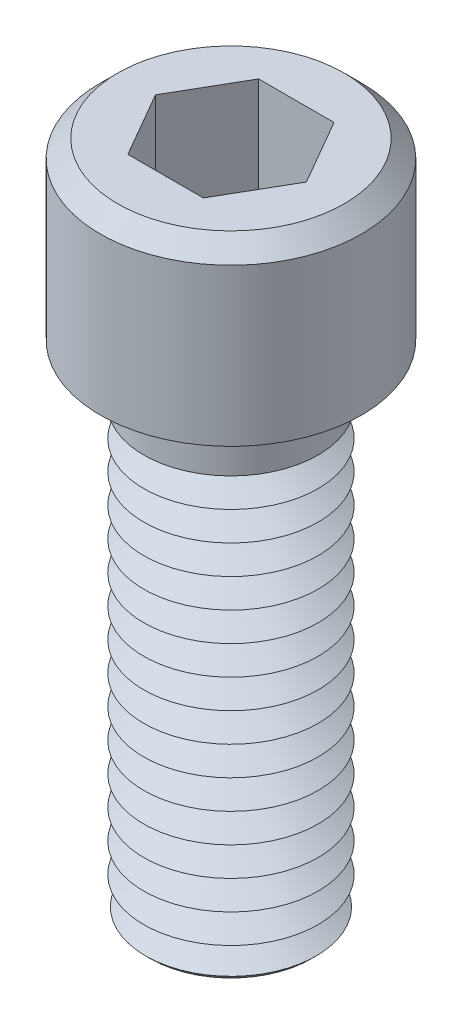
SolidWorks part; units mm, degrees
ref_plane "Front" through (0, 0, 0) normal (0, 0, 1) x (1, 0, 0)
ref_plane "Top" through (0, 0, 0) normal (0, 1, 0) x (1, 0, 0)
ref_plane "Right" through (0, 0, 0) normal (1, 0, 0) x (0, 0, -1)
ref_axis "Axis1" through (0, -50, 0) along (0, 1, 0)
sketch "Sketch ( driver )" plane through (0, 0, 0) normal (0, 0, 1) x (1, 0, 0)
  line L0 (0, 2.1844) -> (1.4199, 2.1844)
  line L1 (1.6383, 1.966) -> (1.4199, 2.1844)
  line L2 (1.6383, 1.966) -> (1.6383, 0)
  line L3 (1.6383, 0) -> (1.0922, 0)
  line L4 (1.0922, 0) -> (1.0922, -6.1316)
  line L5 (1.0922, -6.1316) -> (0.8738, -6.35)
  line L6 (0.8738, -6.35) -> (0, -6.35)
  line L7 (0, -6.35) -> (0, 2.1844)
  line L8 (0, 4.3688) -> (0, 2.1844) construction
  line L9 (1.0922, -0.707) -> (1.0922, -1.071) construction
  line L10 (1.0922, -1.071) -> (0.7769, -0.889) construction
  line L11 (0.7769, -0.889) -> (1.0922, -0.707) construction
  circle A0 centre (0, 2.1844) radius 0.8192 construction
  point P2 (0, 0.6553)
  point P12 (0.8192, 2.1844)
  dimension "D4" = 1.5291
  dimension "D5" = 1.6383
  dimension "D1" = 0.2184
  dimension "Pitch" = 0.3641
  dimension "D2" = 45
  dimension "D3" = 45
  dimension "Diam" = 2.1844
  dimension "Head Dia" = 3.2766
  dimension "Thick" = 2.1844
  dimension "Length" = 6.35
  dimension "End Chamfer" = 0.2184
  dimension "Threaded" = 5.461
sketch "Sketch3" plane through (0, 0, 0) normal (0, 0, 1) x (1, 0, 0)
  line L8 (0, 0.6553) -> (0, -6.35)
  line L9 (0, -6.35) -> (0.8738, -6.35)
  line L10 (0.8738, -6.35) -> (1.0922, -6.1316)
  line L11 (1.0922, -6.1316) -> (1.0922, 0.6553)
  line L12 (1.0922, 0.6553) -> (0, 0.6553)
revolve "Shank Revolve ( driven )" add sketch "Sketch3" angle 360 about axis through (0, -50, 0) along (0, 1, 0)
sketch "Sketch4" plane through (0, 0, 0) normal (0, 0, 1) x (1, 0, 0)
  line L0 (0.7769, -0.889) -> (1.0922, -0.707)
  line L1 (1.0922, -0.707) -> (1.6337, -0.707)
  line L2 (1.6337, -0.707) -> (1.6337, -7.2602)
  line L3 (0.7769, -0.889) -> (1.0922, -1.071)
  line L4 (1.0922, -1.071) -> (0.7769, -1.2531)
  line L5 (0.7769, -1.2531) -> (1.0922, -1.4351)
  line L6 (1.0922, 0) -> (1.0922, -6.1316) construction
  line L7 (1.0922, -1.4351) -> (0.7769, -1.6171)
  line L8 (0.7769, -1.6171) -> (1.0922, -1.7992)
  line L9 (1.0922, -1.7992) -> (0.7769, -1.9812)
  line L10 (0.7769, -1.9812) -> (1.0922, -2.1632)
  line L11 (1.0922, -2.1632) -> (0.7769, -2.3453)
  line L12 (0.7769, -2.3453) -> (1.0922, -2.5273)
  line L13 (1.0922, -2.5273) -> (0.7769, -2.7093)
  line L14 (0.7769, -2.7093) -> (1.0922, -2.8914)
  line L15 (1.0922, -2.8914) -> (0.7769, -3.0734)
  line L16 (0.7769, -3.0734) -> (1.0922, -3.2554)
  line L17 (1.0922, -3.2554) -> (0.7769, -3.4375)
  line L18 (0.7769, -3.4375) -> (1.0922, -3.6195)
  line L19 (1.0922, -3.6195) -> (0.7769, -3.8015)
  line L20 (0.7769, -3.8015) -> (1.0922, -3.9836)
  line L21 (1.0922, -3.9836) -> (0.7769, -4.1656)
  line L22 (0.7769, -4.1656) -> (1.0922, -4.3476)
  line L23 (1.0922, -4.3476) -> (0.7769, -4.5297)
  line L24 (0.7769, -4.5297) -> (1.0922, -4.7117)
  line L25 (1.0922, -4.7117) -> (0.7769, -4.8937)
  line L26 (0.7769, -4.8937) -> (1.0922, -5.0758)
  line L27 (1.0922, -5.0758) -> (0.7769, -5.2578)
  line L28 (0.7769, -5.2578) -> (1.0922, -5.4398)
  line L29 (1.0922, -5.4398) -> (0.7769, -5.6219)
  line L30 (0.7769, -5.6219) -> (1.0922, -5.8039)
  line L31 (1.0922, -5.8039) -> (0.7769, -5.9859)
  line L32 (0.7769, -5.9859) -> (1.0922, -6.168)
  line L33 (1.0922, -6.168) -> (0.7769, -6.35)
  line L34 (0.7769, -6.35) -> (1.0922, -6.532)
  line L35 (1.0922, -6.532) -> (0.7769, -6.7141)
  line L36 (0.7769, -6.7141) -> (1.0922, -6.8961)
  line L37 (1.0922, -6.8961) -> (0.7769, -7.0781)
  line L38 (0.7769, -7.0781) -> (1.0922, -7.2602)
  line L39 (1.0922, -7.2602) -> (1.6337, -7.2602)
revolve "Thread Revolve Cut ( driven )" cut sketch "Sketch4" angle 360 about axis through (0, -50, 0) along (0, 1, 0)
sketch "Sketch5" plane through (0, 0, 0) normal (0, 0, 1) x (1, 0, 0)
  line L0 (0, 2.1844) -> (0, 0)
  line L1 (0, 0) -> (1.6383, 0)
  line L2 (1.6383, 0) -> (1.6383, 1.966)
  line L3 (1.6383, 1.966) -> (1.4199, 2.1844)
  line L4 (1.4199, 2.1844) -> (0, 2.1844)
revolve "Head Revolve ( driven )" add sketch "Sketch5" angle 360 about axis through (0, -50, 0) along (0, 1, 0)
sketch "Sketch2" plane through (0, 2.1844, 0) normal (0, 1, 0) x (-1, 0, 0)
  line L1 (-0.9459, 0) -> (-0.4729, -0.8191)
  line L2 (-0.4729, -0.8191) -> (0.4729, -0.8192)
  line L3 (0.4729, -0.8192) -> (0.9459, 0)
  line L4 (0.9459, 0) -> (0.4729, 0.8191)
  line L5 (0.4729, 0.8191) -> (-0.4729, 0.8192)
  line L6 (-0.4729, 0.8192) -> (-0.9459, 0)
  circle A0 centre (0, 0) radius 0.8192 construction
extrude "Hex Cut ( driven )" cut sketch "Sketch2" against normal up to vertex (1.5291 mm away) up to point (0, 0.6553, 0)
equation "\"Thick@Sketch ( driver )\" = \"Diam@Sketch ( driver )\""
equation "\"D1@Sketch ( driver )\" = .1 * \"Diam@Sketch ( driver )\""
equation "\"Pitch@Sketch ( driver )\" =  \"Diam@Sketch ( driver )\"/6"
equation "\"D4@Sketch ( driver )\" = .7*\"Diam@Sketch ( driver )\""
equation "\"End Chamfer@Sketch ( driver )\" = .1*\"Diam@Sketch ( driver )\""
equation "\"D5@Sketch ( driver )\" = .75 * \"Diam@Sketch ( driver )\""
equation "\"Threaded@Sketch ( driver )\" = 2.5*\"Diam@Sketch ( driver )\""
equation "\"Head Dia@Sketch ( driver )\" = 1.5 * \"Diam@Sketch ( driver )\""
